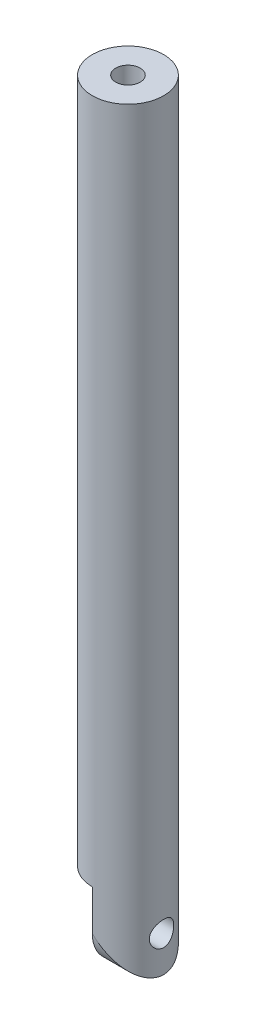
SolidWorks part; units mm, degrees
ref_plane "Front Plane" through (0, 0, 0) normal (0, 0, 1) x (1, 0, 0)
ref_plane "Top Plane" through (0, 0, 0) normal (0, 1, 0) x (1, 0, 0)
ref_plane "Right Plane" through (0, 0, 0) normal (1, 0, 0) x (0, 0, -1)
sketch "Croquis1" plane through (0, 0, 0) normal (0, 1, 0) x (1, 0, 0)
  circle A0 centre (0, 0) radius 9.525
  dimension "D1" = 19.05
extrude "Saliente-Extruir1" add sketch "Croquis1" along normal mid plane 203.2
sketch "Croquis2" plane through (0, 0, 0) normal (1, 0, 0) x (0, 0, -1)
  line L0 (9.525, -101.6) -> (9.525, 101.6) construction
  line L1 (9.525, -81.28) -> (-9.525, -81.28)
  line L2 (9.525, -81.28) -> (9.525, -101.6)
  line L3 (9.525, -101.6) -> (-9.525, -101.6)
  line L4 (-9.525, -81.28) -> (-9.525, -101.6)
  line L5 (-9.525, -101.6) -> (9.525, -101.6) construction
  line L6 (-9.525, 101.6) -> (-9.525, -101.6) construction
  dimension "D1" = 20.32
extrude "Cortar-Extruir1" cut sketch "Croquis2" against normal blind 12.7
sketch "Croquis3" plane through (0, 0, 0) normal (-1, 0, 0) x (0, 0, 1)
  line L0 (-9.525, -101.6) -> (-9.525, -81.28) construction
  line L1 (9.525, -81.28) -> (9.525, -101.6) construction
  line L2 (9.525, -101.6) -> (-9.525, -101.6) construction
  line L3 (-16.045, -92.075) -> (28.0476, -92.075) construction
  line L4 (-9.525, -92.075) -> (-9.525, -101.6)
  line L5 (-9.525, -101.6) -> (0, -101.6)
  line L6 (9.525, -92.075) -> (9.525, -101.6)
  line L7 (9.525, -101.6) -> (0, -101.6)
  arc A0 (-9.525, -92.075) -> (9.525, -92.075) centre (0, -92.075) ccw
  line M1 (-9.525, -81.28) -> (-9.525, -101.6)
  line M2 (-9.525, -101.6) -> (9.525, -101.6)
  line M3 (9.525, -101.6) -> (9.525, -81.28)
extrude "Cortar-Extruir2" cut sketch "Croquis3" against normal blind 12.7 contours A0 M1 M2 | A0 M2 M3
hole_wizard "Taladro roscado 5/16-181" positions "Croquis5" profile "Croquis4" tap size "5/16-18" standard "Ansi Inch"
sketch "Croquis5" plane through (0, 0, 0) normal (-1, 0, 0) x (0, 0, 1)
  point P0 (0, -92.075)
sketch "Croquis4" plane through (0, -92.075, 0) normal (0, 1, 0) x (0, 0, 1)
  line L0 (0, 0) -> (0, 24.8846)
  line L1 (0, 24.8846) -> (3.2639, 22.9235)
  line L2 (3.2639, 22.9235) -> (3.2639, 0)
  line L5 (3.2639, 0) -> (0, 0)
  line L10 (0, 24.8846) -> (-3.2639, 22.9235) construction
  line L11 (0, -6.35) -> (0, 107.95) construction
  dimension "Diámetro de perforador para roscar" = 6.5278
  dimension "Profundidad de perforador para roscar" = 22.9235
  dimension "Ángulo de perforador" = 118
cosmetic thread "Rosca de taladro1" parameters "D1"=12.7, "D2"=7.9375
hole_wizard "Taladro roscado 5/16-182" positions "Croquis7" profile "Croquis6" tap size "5/16-18" standard "Ansi Inch"
sketch "Croquis7" plane through (0, 101.6, 0) normal (0, 1, 0) x (1, 0, 0)
  point P0 (0, 0)
sketch "Croquis6" plane through (0, 101.6, 0) normal (1, 0, 0) x (0, 0, 1)
  line L0 (0, 0) -> (0, 21.7096)
  line L1 (0, 21.7096) -> (3.2639, 19.7485)
  line L2 (3.2639, 19.7485) -> (3.2639, 0)
  line L5 (3.2639, 0) -> (0, 0)
  line L10 (0, 21.7096) -> (-3.2639, 19.7485) construction
  line L11 (0, -6.35) -> (0, 107.95) construction
  dimension "Diámetro de perforador para roscar" = 6.5278
  dimension "Profundidad de perforador para roscar" = 19.7485
  dimension "Ángulo de perforador" = 118
cosmetic thread "Rosca de taladro2" parameters "D1"=12.7, "D2"=7.9375
